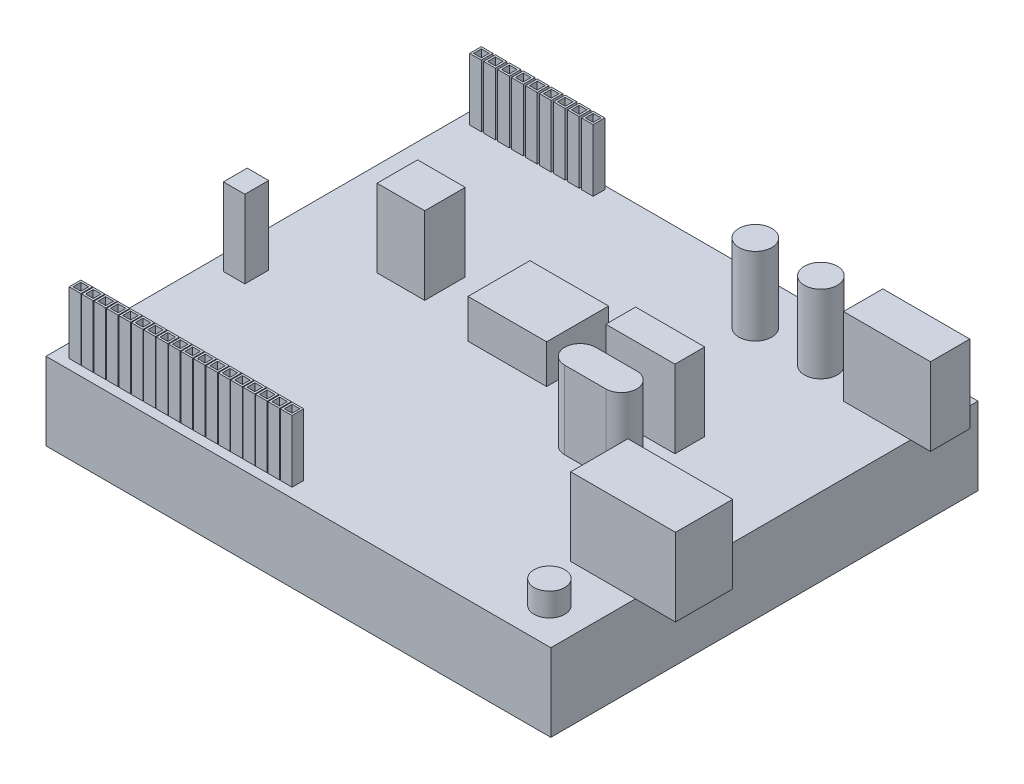
SolidWorks part; units mm, degrees
ref_plane "Front Plane" through (0, 0, 0) normal (0, 0, 1) x (1, 0, 0)
ref_plane "Top Plane" through (0, 0, 0) normal (0, 1, 0) x (1, 0, 0)
ref_plane "Right Plane" through (0, 0, 0) normal (1, 0, 0) x (0, 0, -1)
sketch "Sketch1" plane through (0, 0, 0) normal (0, 1, 0) x (1, 0, 0)
  line L1 (-32.5, 27.5) -> (32.5, 27.5)
  line L2 (-32.5, 27.5) -> (-32.5, -27.5)
  line L3 (-32.5, -27.5) -> (32.5, -27.5)
  line L4 (32.5, 27.5) -> (32.5, -27.5)
  line L5 (-32.5, 27.5) -> (32.5, -27.5) construction
  line L6 (-32.5, -27.5) -> (32.5, 27.5) construction
  point P0 (0, 0)
  dimension "D1" = 55
  dimension "D2" = 65
extrude "Boss-Extrude1" add sketch "Sketch1" along normal blind 10
sketch "Sketch3" plane through (0, 10, 0) normal (0, 1, 0) x (1, 0, 0)
  line L0 (-28.9021, -26.0144) -> (-27.9021, -26.0144)
  line L1 (-30.7521, -24.7644) -> (-29.2521, -24.7644)
  line L2 (-30.7521, -24.7644) -> (-30.7521, -26.2644)
  line L3 (-30.7521, -26.2644) -> (-29.2521, -26.2644)
  line L4 (-29.2521, -24.7644) -> (-29.2521, -26.2644)
  line L5 (-30.7521, -24.7644) -> (-29.2521, -26.2644) construction
  line L6 (-30.7521, -26.2644) -> (-29.2521, -24.7644) construction
  line L7 (-30.5021, -25.0144) -> (-29.5021, -25.0144)
  line L8 (-30.5021, -25.0144) -> (-30.5021, -26.0144)
  line L9 (-30.5021, -26.0144) -> (-29.5021, -26.0144)
  line L10 (-29.5021, -25.0144) -> (-29.5021, -26.0144)
  line L11 (-30.5021, -25.0144) -> (-29.5021, -26.0144) construction
  line L12 (-30.5021, -26.0144) -> (-29.5021, -25.0144) construction
  line L13 (-28.9021, -25.0144) -> (-28.9021, -26.0144)
  line L14 (-28.9021, -25.0144) -> (-27.9021, -25.0144)
  line L15 (-27.9021, -25.0144) -> (-27.9021, -26.0144)
  line L16 (-29.1521, -24.7644) -> (-29.1521, -26.2644)
  line L17 (-27.6521, -24.7644) -> (-27.6521, -26.2644)
  line L18 (-29.1521, -24.7644) -> (-27.6521, -24.7644)
  line L19 (-29.1521, -26.2644) -> (-27.6521, -26.2644)
  line L20 (-27.3021, -26.0144) -> (-26.3021, -26.0144)
  line L21 (-27.3021, -25.0144) -> (-27.3021, -26.0144)
  line L22 (-27.3021, -25.0144) -> (-26.3021, -25.0144)
  line L23 (-26.3021, -25.0144) -> (-26.3021, -26.0144)
  line L24 (-27.5521, -24.7644) -> (-27.5521, -26.2644)
  line L25 (-26.0521, -24.7644) -> (-26.0521, -26.2644)
  line L26 (-27.5521, -24.7644) -> (-26.0521, -24.7644)
  line L27 (-27.5521, -26.2644) -> (-26.0521, -26.2644)
  line L28 (-25.7021, -26.0144) -> (-24.7021, -26.0144)
  line L29 (-25.7021, -25.0144) -> (-25.7021, -26.0144)
  line L30 (-25.7021, -25.0144) -> (-24.7021, -25.0144)
  line L31 (-24.7021, -25.0144) -> (-24.7021, -26.0144)
  line L32 (-25.9521, -24.7644) -> (-25.9521, -26.2644)
  line L33 (-24.4521, -24.7644) -> (-24.4521, -26.2644)
  line L34 (-25.9521, -24.7644) -> (-24.4521, -24.7644)
  line L35 (-25.9521, -26.2644) -> (-24.4521, -26.2644)
  line L36 (-24.1021, -26.0144) -> (-23.1021, -26.0144)
  line L37 (-24.1021, -25.0144) -> (-24.1021, -26.0144)
  line L38 (-24.1021, -25.0144) -> (-23.1021, -25.0144)
  line L39 (-23.1021, -25.0144) -> (-23.1021, -26.0144)
  line L40 (-24.3521, -24.7644) -> (-24.3521, -26.2644)
  line L41 (-22.8521, -24.7644) -> (-22.8521, -26.2644)
  line L42 (-24.3521, -24.7644) -> (-22.8521, -24.7644)
  line L43 (-24.3521, -26.2644) -> (-22.8521, -26.2644)
  line L44 (-22.5021, -26.0144) -> (-21.5021, -26.0144)
  line L45 (-22.5021, -25.0144) -> (-22.5021, -26.0144)
  line L46 (-22.5021, -25.0144) -> (-21.5021, -25.0144)
  line L47 (-21.5021, -25.0144) -> (-21.5021, -26.0144)
  line L48 (-22.7521, -24.7644) -> (-22.7521, -26.2644)
  line L49 (-21.2521, -24.7644) -> (-21.2521, -26.2644)
  line L50 (-22.7521, -24.7644) -> (-21.2521, -24.7644)
  line L51 (-22.7521, -26.2644) -> (-21.2521, -26.2644)
  line L52 (-20.9021, -26.0144) -> (-19.9021, -26.0144)
  line L53 (-20.9021, -25.0144) -> (-20.9021, -26.0144)
  line L54 (-20.9021, -25.0144) -> (-19.9021, -25.0144)
  line L55 (-19.9021, -25.0144) -> (-19.9021, -26.0144)
  line L56 (-21.1521, -24.7644) -> (-21.1521, -26.2644)
  line L57 (-19.6521, -24.7644) -> (-19.6521, -26.2644)
  line L58 (-21.1521, -24.7644) -> (-19.6521, -24.7644)
  line L59 (-21.1521, -26.2644) -> (-19.6521, -26.2644)
  line L60 (-19.3021, -26.0144) -> (-18.3021, -26.0144)
  line L61 (-19.3021, -25.0144) -> (-19.3021, -26.0144)
  line L62 (-19.3021, -25.0144) -> (-18.3021, -25.0144)
  line L63 (-18.3021, -25.0144) -> (-18.3021, -26.0144)
  line L64 (-19.5521, -24.7644) -> (-19.5521, -26.2644)
  line L65 (-18.0521, -24.7644) -> (-18.0521, -26.2644)
  line L66 (-19.5521, -24.7644) -> (-18.0521, -24.7644)
  line L67 (-19.5521, -26.2644) -> (-18.0521, -26.2644)
  line L68 (-17.7021, -26.0144) -> (-16.7021, -26.0144)
  line L69 (-17.7021, -25.0144) -> (-17.7021, -26.0144)
  line L70 (-17.7021, -25.0144) -> (-16.7021, -25.0144)
  line L71 (-16.7021, -25.0144) -> (-16.7021, -26.0144)
  line L72 (-17.9521, -24.7644) -> (-17.9521, -26.2644)
  line L73 (-16.4521, -24.7644) -> (-16.4521, -26.2644)
  line L74 (-17.9521, -24.7644) -> (-16.4521, -24.7644)
  line L75 (-17.9521, -26.2644) -> (-16.4521, -26.2644)
  line L76 (-16.1021, -26.0144) -> (-15.1021, -26.0144)
  line L77 (-16.1021, -25.0144) -> (-16.1021, -26.0144)
  line L78 (-16.1021, -25.0144) -> (-15.1021, -25.0144)
  line L79 (-15.1021, -25.0144) -> (-15.1021, -26.0144)
  line L80 (-16.3521, -24.7644) -> (-16.3521, -26.2644)
  line L81 (-14.8521, -24.7644) -> (-14.8521, -26.2644)
  line L82 (-16.3521, -24.7644) -> (-14.8521, -24.7644)
  line L83 (-16.3521, -26.2644) -> (-14.8521, -26.2644)
  line L84 (-14.5021, -26.0144) -> (-13.5021, -26.0144)
  line L85 (-14.5021, -25.0144) -> (-14.5021, -26.0144)
  line L86 (-14.5021, -25.0144) -> (-13.5021, -25.0144)
  line L87 (-13.5021, -25.0144) -> (-13.5021, -26.0144)
  line L88 (-14.7521, -24.7644) -> (-14.7521, -26.2644)
  line L89 (-13.2521, -24.7644) -> (-13.2521, -26.2644)
  line L90 (-14.7521, -24.7644) -> (-13.2521, -24.7644)
  line L91 (-14.7521, -26.2644) -> (-13.2521, -26.2644)
  line L92 (-12.9021, -26.0144) -> (-11.9021, -26.0144)
  line L93 (-12.9021, -25.0144) -> (-12.9021, -26.0144)
  line L94 (-12.9021, -25.0144) -> (-11.9021, -25.0144)
  line L95 (-11.9021, -25.0144) -> (-11.9021, -26.0144)
  line L96 (-13.1521, -24.7644) -> (-13.1521, -26.2644)
  line L97 (-11.6521, -24.7644) -> (-11.6521, -26.2644)
  line L98 (-13.1521, -24.7644) -> (-11.6521, -24.7644)
  line L99 (-13.1521, -26.2644) -> (-11.6521, -26.2644)
  line L100 (-11.3021, -26.0144) -> (-10.3021, -26.0144)
  line L101 (-11.3021, -25.0144) -> (-11.3021, -26.0144)
  line L102 (-11.3021, -25.0144) -> (-10.3021, -25.0144)
  line L103 (-10.3021, -25.0144) -> (-10.3021, -26.0144)
  line L104 (-11.5521, -24.7644) -> (-11.5521, -26.2644)
  line L105 (-10.0521, -24.7644) -> (-10.0521, -26.2644)
  line L106 (-11.5521, -24.7644) -> (-10.0521, -24.7644)
  line L107 (-11.5521, -26.2644) -> (-10.0521, -26.2644)
  line L108 (-9.7021, -26.0144) -> (-8.7021, -26.0144)
  line L109 (-9.7021, -25.0144) -> (-9.7021, -26.0144)
  line L110 (-9.7021, -25.0144) -> (-8.7021, -25.0144)
  line L111 (-8.7021, -25.0144) -> (-8.7021, -26.0144)
  line L112 (-9.9521, -24.7644) -> (-9.9521, -26.2644)
  line L113 (-8.4521, -24.7644) -> (-8.4521, -26.2644)
  line L114 (-9.9521, -24.7644) -> (-8.4521, -24.7644)
  line L115 (-9.9521, -26.2644) -> (-8.4521, -26.2644)
  line L116 (-8.1021, -26.0144) -> (-7.1021, -26.0144)
  line L117 (-8.1021, -25.0144) -> (-8.1021, -26.0144)
  line L118 (-8.1021, -25.0144) -> (-7.1021, -25.0144)
  line L119 (-7.1021, -25.0144) -> (-7.1021, -26.0144)
  line L120 (-8.3521, -24.7644) -> (-8.3521, -26.2644)
  line L121 (-6.8521, -24.7644) -> (-6.8521, -26.2644)
  line L122 (-8.3521, -24.7644) -> (-6.8521, -24.7644)
  line L123 (-8.3521, -26.2644) -> (-6.8521, -26.2644)
  line L124 (-6.5021, -26.0144) -> (-5.5021, -26.0144)
  line L125 (-6.5021, -25.0144) -> (-6.5021, -26.0144)
  line L126 (-6.5021, -25.0144) -> (-5.5021, -25.0144)
  line L127 (-5.5021, -25.0144) -> (-5.5021, -26.0144)
  line L128 (-6.7521, -24.7644) -> (-6.7521, -26.2644)
  line L129 (-5.2521, -24.7644) -> (-5.2521, -26.2644)
  line L130 (-6.7521, -24.7644) -> (-5.2521, -24.7644)
  line L131 (-6.7521, -26.2644) -> (-5.2521, -26.2644)
  line L132 (-4.9021, -26.0144) -> (-3.9021, -26.0144)
  line L133 (-4.9021, -25.0144) -> (-4.9021, -26.0144)
  line L134 (-4.9021, -25.0144) -> (-3.9021, -25.0144)
  line L135 (-3.9021, -25.0144) -> (-3.9021, -26.0144)
  line L136 (-5.1521, -24.7644) -> (-5.1521, -26.2644)
  line L137 (-3.6521, -24.7644) -> (-3.6521, -26.2644)
  line L138 (-5.1521, -24.7644) -> (-3.6521, -24.7644)
  line L139 (-5.1521, -26.2644) -> (-3.6521, -26.2644)
  line L140 (-3.3021, -26.0144) -> (-2.3021, -26.0144)
  line L141 (-3.3021, -25.0144) -> (-3.3021, -26.0144)
  line L142 (-3.3021, -25.0144) -> (-2.3021, -25.0144)
  line L143 (-2.3021, -25.0144) -> (-2.3021, -26.0144)
  line L144 (-3.5521, -24.7644) -> (-3.5521, -26.2644)
  line L145 (-2.0521, -24.7644) -> (-2.0521, -26.2644)
  line L146 (-3.5521, -24.7644) -> (-2.0521, -24.7644)
  line L147 (-3.5521, -26.2644) -> (-2.0521, -26.2644)
  point P0 (-30.0021, -25.5144)
  point P5 (-30.0021, -25.5144)
  dimension "D1" = 1.5
  dimension "D2" = 1.5
  dimension "D3" = 1
  dimension "D4" = 1
  dimension "D5" = 18
extrude "Boss-Extrude3" add sketch "Sketch3" along normal blind 8
sketch "Sketch5" plane through (0, 10, 0) normal (0, 1, 0) x (1, 0, 0)
  line L0 (-29.2021, 27.0509) -> (-27.7021, 27.0509)
  line L1 (-31.0021, 27.0509) -> (-29.5021, 27.0509)
  line L2 (-31.0021, 27.0509) -> (-31.0021, 25.5509)
  line L3 (-31.0021, 25.5509) -> (-29.5021, 25.5509)
  line L4 (-29.5021, 27.0509) -> (-29.5021, 25.5509)
  line L5 (-31.0021, 27.0509) -> (-29.5021, 25.5509) construction
  line L6 (-31.0021, 25.5509) -> (-29.5021, 27.0509) construction
  line L7 (-30.7521, 26.8009) -> (-29.7521, 26.8009)
  line L8 (-30.7521, 26.8009) -> (-30.7521, 25.8009)
  line L9 (-30.7521, 25.8009) -> (-29.7521, 25.8009)
  line L10 (-29.7521, 26.8009) -> (-29.7521, 25.8009)
  line L11 (-30.7521, 26.8009) -> (-29.7521, 25.8009) construction
  line L12 (-30.7521, 25.8009) -> (-29.7521, 26.8009) construction
  line L13 (-27.7021, 27.0509) -> (-27.7021, 25.5509)
  line L14 (-29.2021, 25.5509) -> (-27.7021, 25.5509)
  line L15 (-28.9521, 26.8009) -> (-27.9521, 26.8009)
  line L16 (-28.9521, 25.8009) -> (-27.9521, 25.8009)
  line L17 (-27.9521, 26.8009) -> (-27.9521, 25.8009)
  line L18 (-28.9521, 26.8009) -> (-28.9521, 25.8009)
  line L19 (-27.4021, 27.0509) -> (-25.9021, 27.0509)
  line L20 (-25.9021, 27.0509) -> (-25.9021, 25.5509)
  line L21 (-27.4021, 25.5509) -> (-25.9021, 25.5509)
  line L22 (-27.1521, 26.8009) -> (-26.1521, 26.8009)
  line L23 (-27.1521, 25.8009) -> (-26.1521, 25.8009)
  line L24 (-26.1521, 26.8009) -> (-26.1521, 25.8009)
  line L25 (-27.1521, 26.8009) -> (-27.1521, 25.8009)
  line L26 (-25.6021, 27.0509) -> (-24.1021, 27.0509)
  line L27 (-24.1021, 27.0509) -> (-24.1021, 25.5509)
  line L28 (-25.6021, 25.5509) -> (-24.1021, 25.5509)
  line L29 (-25.3521, 26.8009) -> (-24.3521, 26.8009)
  line L30 (-25.3521, 25.8009) -> (-24.3521, 25.8009)
  line L31 (-24.3521, 26.8009) -> (-24.3521, 25.8009)
  line L32 (-25.3521, 26.8009) -> (-25.3521, 25.8009)
  line L33 (-27.4021, 27.0509) -> (-27.4021, 25.5509)
  line L34 (-29.2021, 27.0509) -> (-29.2021, 25.5509)
  line L35 (-25.6021, 27.0509) -> (-25.6021, 25.5509)
  line L36 (-23.5521, 26.8009) -> (-22.5521, 26.8009)
  line L37 (-23.5521, 26.8009) -> (-23.5521, 25.8009)
  line L38 (-22.5521, 26.8009) -> (-22.5521, 25.8009)
  line L39 (-23.8021, 27.0509) -> (-22.3021, 27.0509)
  line L40 (-22.3021, 27.0509) -> (-22.3021, 25.5509)
  line L41 (-23.8021, 27.0509) -> (-23.8021, 25.5509)
  line L42 (-21.7521, 26.8009) -> (-20.7521, 26.8009)
  line L43 (-21.7521, 26.8009) -> (-21.7521, 25.8009)
  line L44 (-20.7521, 26.8009) -> (-20.7521, 25.8009)
  line L45 (-22.0021, 27.0509) -> (-20.5021, 27.0509)
  line L46 (-20.5021, 27.0509) -> (-20.5021, 25.5509)
  line L47 (-22.0021, 27.0509) -> (-22.0021, 25.5509)
  line L48 (-19.9521, 26.8009) -> (-18.9521, 26.8009)
  line L49 (-19.9521, 26.8009) -> (-19.9521, 25.8009)
  line L50 (-18.9521, 26.8009) -> (-18.9521, 25.8009)
  line L51 (-20.2021, 27.0509) -> (-18.7021, 27.0509)
  line L52 (-18.7021, 27.0509) -> (-18.7021, 25.5509)
  line L53 (-20.2021, 27.0509) -> (-20.2021, 25.5509)
  line L54 (-18.1521, 26.8009) -> (-17.1521, 26.8009)
  line L55 (-18.1521, 26.8009) -> (-18.1521, 25.8009)
  line L56 (-17.1521, 26.8009) -> (-17.1521, 25.8009)
  line L57 (-18.4021, 27.0509) -> (-16.9021, 27.0509)
  line L58 (-16.9021, 27.0509) -> (-16.9021, 25.5509)
  line L59 (-18.4021, 27.0509) -> (-18.4021, 25.5509)
  line L60 (-16.3521, 26.8009) -> (-15.3521, 26.8009)
  line L61 (-16.3521, 26.8009) -> (-16.3521, 25.8009)
  line L62 (-15.3521, 26.8009) -> (-15.3521, 25.8009)
  line L63 (-16.6021, 27.0509) -> (-15.1021, 27.0509)
  line L64 (-15.1021, 27.0509) -> (-15.1021, 25.5509)
  line L65 (-16.6021, 27.0509) -> (-16.6021, 25.5509)
  line L66 (-23.5521, 25.8009) -> (-22.5521, 25.8009)
  line L67 (-21.7521, 25.8009) -> (-20.7521, 25.8009)
  line L68 (-22.0021, 25.5509) -> (-20.5021, 25.5509)
  line L69 (-22.3021, 25.5509) -> (-23.8021, 25.5509)
  line L70 (-19.9521, 25.8009) -> (-18.9521, 25.8009)
  line L71 (-18.1521, 25.8009) -> (-17.1521, 25.8009)
  line L72 (-16.9021, 25.5509) -> (-18.3658, 25.5509)
  line L73 (-18.3658, 25.5509) -> (-18.4021, 25.5509)
  line L74 (-20.2021, 25.5509) -> (-18.7021, 25.5509)
  line L75 (-16.6021, 25.5509) -> (-15.0744, 25.5509)
  line L76 (-16.3521, 25.8009) -> (-15.3521, 25.8009)
  point P0 (-30.2521, 26.3009)
  point P5 (-30.2521, 26.3009)
  dimension "D1" = 1.5
  dimension "D2" = 1
  dimension "D3" = 1.5
  dimension "D4" = 4
  dimension "D5" = 6
extrude "Boss-Extrude4" add sketch "Sketch5" along normal blind 8 contours L65 L75 L64 L63 L76 L61 L60 L62 | L73 L72 L58 L57 L59 L71 L55 L54 L56 | L53 L74 L52 L51 L70 L49 L48 L50 | L47 L68 L46 L45 L67 L43 L42 L44 | L69 L40 L39 L41 L66 L37 L36 L38 | L4 L1 L2 L3 L7 L10 L9 L8 | L22 L25 L23 L24 | L14 L13 L0 L34 | L21 L20 L19 L33 | L28 L27 L26 L35 | L29 L31 L30 L32 | L15 L17 L16 L18
sketch "Sketch6" plane through (0, 10, 0) normal (0, 1, 0) x (1, 0, 0)
  line L0 (11.8887, -3.1064) -> (17.1811, -3.1064) construction
  line L1 (-20.4792, 8.3221) -> (-14.3431, 8.3221)
  line L2 (-20.4792, 8.3221) -> (-20.4792, 3.1064)
  line L3 (-20.4792, 3.1064) -> (-14.3431, 3.1064)
  line L4 (-14.3431, 8.3221) -> (-14.3431, 3.1064)
  line L5 (-20.4792, 8.3221) -> (-14.3431, 3.1064) construction
  line L6 (-20.4792, 3.1064) -> (-14.3431, 8.3221) construction
  line L7 (9.9712, 5.9443) -> (18.8685, 5.9443)
  line L8 (9.9712, 5.9443) -> (9.9712, 2.1093)
  line L9 (9.9712, 2.1093) -> (18.8685, 2.1093)
  line L10 (18.8685, 5.9443) -> (18.8685, 2.1093)
  line L11 (9.9712, 5.9443) -> (18.8685, 2.1093) construction
  line L12 (9.9712, 2.1093) -> (18.8685, 5.9443) construction
  line L13 (24.1609, -9.2425) -> (37.6603, -9.2425)
  line L14 (24.1609, -9.2425) -> (24.1609, -16.6058)
  line L15 (24.1609, -16.6058) -> (37.6603, -16.6058)
  line L16 (37.6603, -9.2425) -> (37.6603, -16.6058)
  line L17 (24.1609, -9.2425) -> (37.6603, -16.6058) construction
  line L18 (24.1609, -16.6058) -> (37.6603, -9.2425) construction
  line L19 (23.8541, 23.8924) -> (35.0525, 23.8924)
  line L20 (23.8541, 23.8924) -> (23.8541, 18.8302)
  line L21 (23.8541, 18.8302) -> (35.0525, 18.8302)
  line L22 (35.0525, 23.8924) -> (35.0525, 18.8302)
  line L23 (23.8541, 23.8924) -> (35.0525, 18.8302) construction
  line L24 (23.8541, 18.8302) -> (35.0525, 23.8924) construction
  line L25 (11.8887, -1.1122) -> (17.1811, -1.1122)
  line L26 (11.8887, -5.1006) -> (17.1811, -5.1006)
  line L28 (-30.5271, -3.5666) -> (-27.7658, -3.5666)
  line L29 (-30.5271, -3.5666) -> (-30.5271, -6.6347)
  line L30 (-30.5271, -6.6347) -> (-27.7658, -6.6347)
  line L31 (-27.7658, -3.5666) -> (-27.7658, -6.6347)
  line L32 (-30.5271, -3.5666) -> (-27.7658, -6.6347) construction
  line L33 (-30.5271, -6.6347) -> (-27.7658, -3.5666) construction
  arc A0 (11.8887, -1.1122) -> (11.8887, -5.1006) centre (11.8887, -3.1064) ccw
  arc A1 (17.1811, -5.1006) -> (17.1811, -1.1122) centre (17.1811, -3.1064) ccw
  circle A2 centre (9.9712, 21.3613) radius 2.127
  circle A3 centre (18.4083, 21.3613) radius 2.127
  point P0 (-17.4112, 5.7142)
  point P5 (14.4198, 4.0268)
  point P10 (30.9106, -12.9242)
  point P15 (29.4533, 21.3613)
  point P22 (14.5349, -3.1064)
  point P31 (-29.1465, -5.1006)
extrude "Boss-Extrude5" add sketch "Sketch6" along normal blind 10 contours L20 L19 L22 L21 | L14 L13 L16 L15 | L26 A1 L25 A0 | L8 L7 L10 L9 | A2 | A3 | L2 L1 L4 L3 | L29 L28 L31 L30
sketch "Sketch7" plane through (0, 10, 0) normal (0, 1, 0) x (1, 0, 0)
  circle A0 centre (27.7004, -22.8812) radius 1.9802
extrude "Boss-Extrude6" add sketch "Sketch7" along normal blind 3
sketch "Sketch8" plane through (0, 10, 0) normal (0, 1, 0) x (1, 0, 0)
  line L1 (-7.0075, 9.3192) -> (3.1171, 9.3192)
  line L2 (-7.0075, 9.3192) -> (-7.0075, 1.3423)
  line L3 (-7.0075, 1.3423) -> (3.1171, 1.3423)
  line L4 (3.1171, 9.3192) -> (3.1171, 1.3423)
  line L5 (-7.0075, 9.3192) -> (3.1171, 1.3423) construction
  line L6 (-7.0075, 1.3423) -> (3.1171, 9.3192) construction
extrude "Boss-Extrude7" add sketch "Sketch8" along normal blind 5
